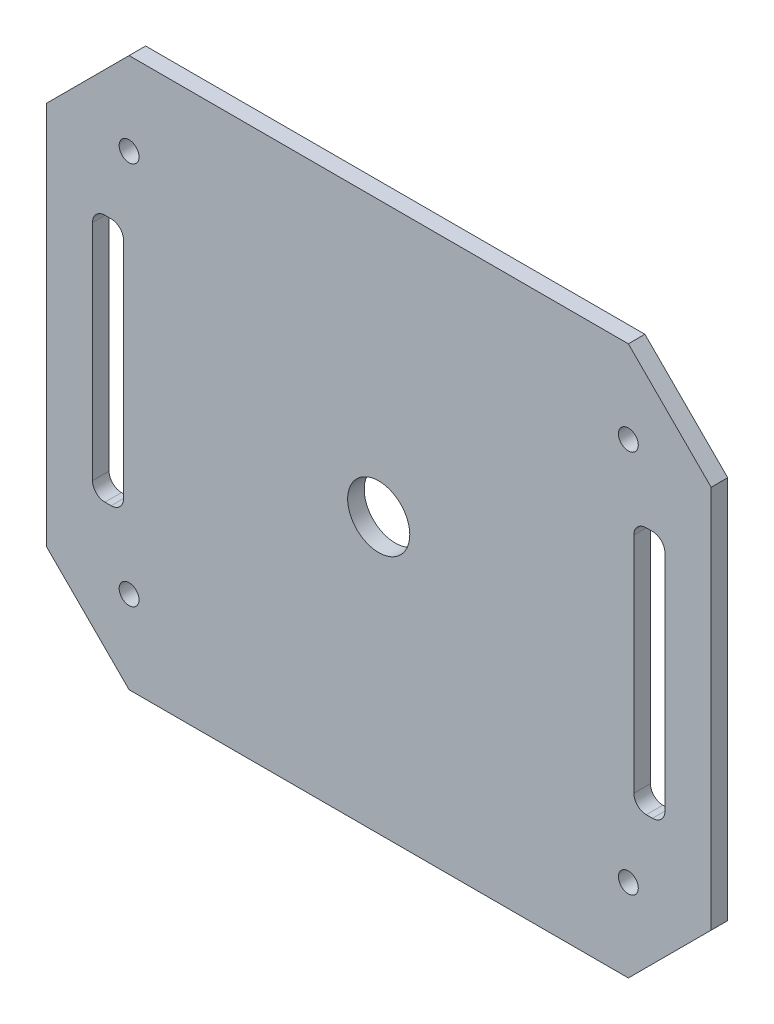
SolidWorks part; units mm, degrees
ref_plane "Front Plane" through (0, 0, 0) normal (0, 0, 1) x (1, 0, 0)
ref_plane "Top Plane" through (0, 0, 0) normal (0, 1, 0) x (1, 0, 0)
ref_plane "Right Plane" through (0, 0, 0) normal (1, 0, 0) x (0, 0, -1)
sketch "Sketch1" plane through (0, 0, 0) normal (0, 0, 1) x (1, 0, 0)
  line L0 (-14.8357, -38.0756) -> (0.1643, -23.0756)
  line L1 (0.1643, -23.0756) -> (90.5883, -23.0756)
  line L2 (90.5883, -23.0756) -> (105.5883, -38.0756)
  line L3 (-14.8357, -107.5446) -> (0.1643, -122.5446)
  line L4 (0.1643, -122.5446) -> (90.5883, -122.5446)
  line L5 (90.5883, -122.5446) -> (105.5883, -107.5446)
  line L6 (-14.8357, -38.0756) -> (-14.8357, -107.5446)
  line L7 (-4.2107, -50.3101) -> (-3.0857, -50.3101)
  line L8 (-6.4607, -52.5601) -> (-6.4607, -93.0601)
  line L9 (-4.2107, -95.3101) -> (-3.0857, -95.3101)
  line L10 (-0.8357, -52.5601) -> (-0.8357, -93.0601)
  line L11 (94.9633, -50.3101) -> (93.8383, -50.3101)
  line L12 (97.2133, -52.5601) -> (97.2133, -93.0601)
  line L13 (94.9633, -95.3101) -> (93.8383, -95.3101)
  line L14 (91.5883, -52.5601) -> (91.5883, -93.0601)
  line L15 (105.5883, -38.0756) -> (105.5883, -107.5446)
  arc A0 (97.2133, -52.5601) -> (94.9633, -50.3101) centre (94.9633, -52.5601) ccw
  arc A1 (93.8383, -50.3101) -> (91.5883, -52.5601) centre (93.8383, -52.5601) ccw
  arc A2 (94.9633, -95.3101) -> (97.2133, -93.0601) centre (94.9633, -93.0601) ccw
  arc A3 (91.5883, -93.0601) -> (93.8383, -95.3101) centre (93.8383, -93.0601) ccw
  arc A4 (-3.0857, -95.3101) -> (-0.8357, -93.0601) centre (-3.0857, -93.0601) ccw
  arc A5 (-6.4607, -93.0601) -> (-4.2107, -95.3101) centre (-4.2107, -93.0601) ccw
  arc A6 (-0.8357, -52.5601) -> (-3.0857, -50.3101) centre (-3.0857, -52.5601) ccw
  arc A7 (-4.2107, -50.3101) -> (-6.4607, -52.5601) centre (-4.2107, -52.5601) ccw
  circle A8 centre (0.1643, -38.0756) radius 1.8
  circle A9 centre (90.5883, -38.0756) radius 1.8
  circle A10 centre (90.5883, -107.5446) radius 1.8
  circle A11 centre (0.1643, -107.5446) radius 1.8
  circle A12 centre (45.3763, -72.8101) radius 5.625
  point P42 (0, 0)
  point P43 (0, 0)
  point P44 (0, 0)
  point P45 (0, 0)
  point P46 (0, 0)
  point P47 (0, 0)
  point P48 (0, 0)
  point P49 (0, 0)
  point P50 (0, 0)
  point P51 (48.9548, -33.223)
  point P52 (0, 0)
  point P53 (0, 0)
  point P54 (0, 0)
  point P55 (0, 0)
  point P56 (0, 0)
  point P57 (0, 0)
  point P58 (0, 0)
  point P59 (0, 0)
  point P60 (91.5883, -72.8101)
  point P61 (-0.8357, -72.8101)
  point P62 (45.3763, -23.0756)
  point P63 (0, 0)
  point P64 (-14.8357, -72.8101)
  point P65 (105.5883, -72.8101)
  dimension "D1" = 90.424
  dimension "D2" = 69.469
  dimension "D3" = 15
  dimension "D4" = 15
  dimension "D5" = 15
  dimension "D6" = 15
  dimension "D7" = 40.5
  dimension "D8" = 49.7345
  dimension "D9" = 14
  dimension "D10" = 14
extrude "Boss-Extrude1" add sketch "Sketch1" along normal blind 3
